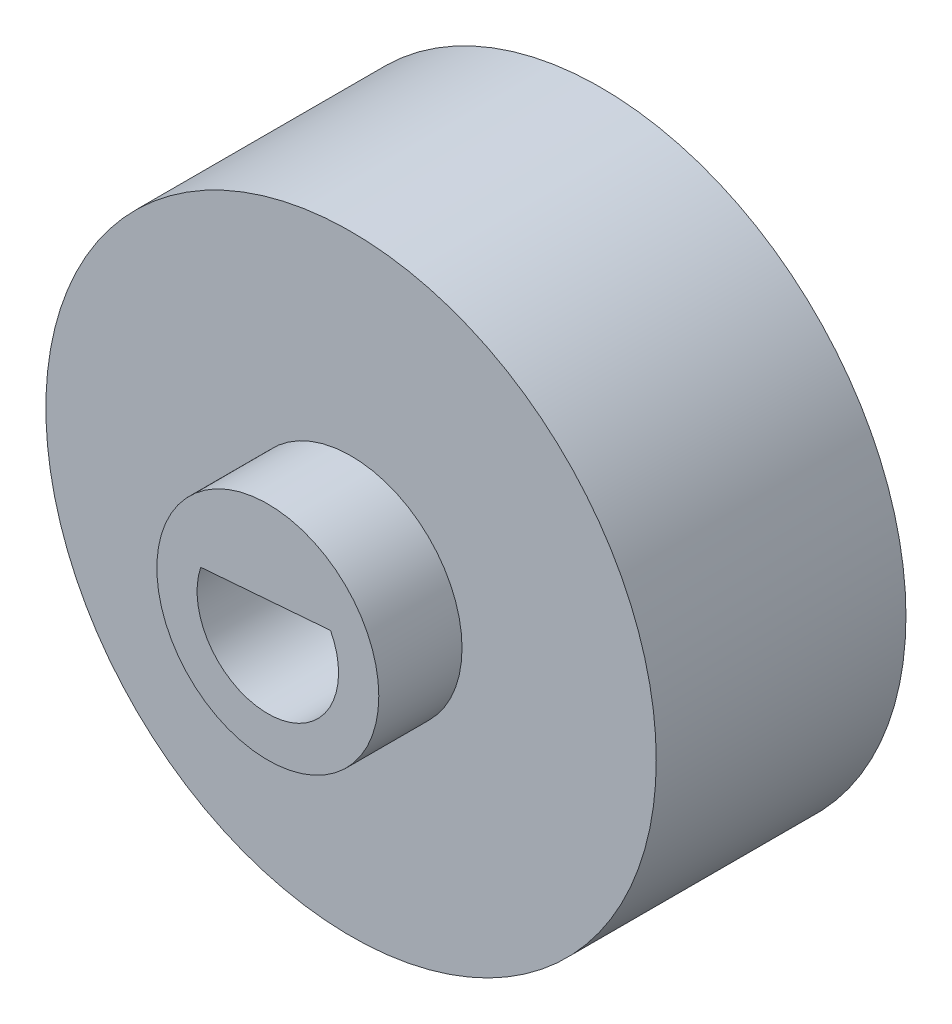
SolidWorks part; units mm, degrees
ref_plane "前视基准面" through (0, 0, 0) normal (0, 0, 1) x (1, 0, 0)
ref_plane "上视基准面" through (0, 0, 0) normal (0, 1, 0) x (1, 0, 0)
ref_plane "右视基准面" through (0, 0, 0) normal (1, 0, 0) x (0, 0, -1)
other "Configuration Table"
sketch "草图1" plane through (0, 0, 0) normal (0, 0, 1) x (1, 0, 0)
  line L0 (4.5201, 2.3619) -> (-4.8339, 1.6257)
  circle A0 centre (0, 0) radius 8
  arc A1 (-4.8339, 1.6257) -> (4.5201, 2.3619) centre (0, 0) ccw
extrude "凸台-拉伸1" add sketch "草图1" along normal blind 24
sketch "草图2" plane through (0, 0, 0) normal (0, 0, 1) x (1, 0, 0)
  circle A0 centre (0, 0) radius 22
  circle A1 centre (0, 0) radius 8
extrude "凸台-拉伸2" add sketch "草图2" along normal blind 18
sketch "草图3" plane through (0, 0, 0) normal (0, 0, 1) x (1, 0, 0)
  line L0 (17.4237, 1.6329) -> (18.7119, 1.6329)
  line L1 (18.7119, 1.6329) -> (18.7557, 1.7557)
  line L2 (18.7557, 1.7557) -> (18.8873, 1.754)
  line L3 (18.8873, 1.754) -> (19.1059, 1.7366)
  line L4 (19.1059, 1.7366) -> (19.4097, 1.7366)
  line L5 (19.4097, 1.7366) -> (19.7954, 1.7366)
  line L6 (19.7954, 1.7366) -> (20.2587, 1.7366)
  line L7 (20.2587, 1.7366) -> (20.7568, 1.2385)
  line L8 (20.7568, 1.2385) -> (21.395, 1.2385)
  line L9 (21.9651, 1.2385) -> (21.9939, 0.5176)
  line L10 (21.9939, 0.5176) -> (22, 0)
  line L11 (22, 0) -> (21.9939, -0.5176)
  line L12 (21.9939, -0.5176) -> (21.9756, -1.0349)
  line L13 (21.9756, -1.0349) -> (20.7568, -1.0349)
  line L14 (20.7568, -1.0349) -> (20.2587, -1.533)
  line L15 (20.2587, -1.533) -> (19.7954, -1.533)
  line L16 (19.7954, -1.533) -> (19.4097, -1.533)
  line L17 (19.4097, -1.533) -> (19.1059, -1.533)
  line L18 (19.1059, -1.533) -> (18.8873, -1.754)
  line L19 (18.8873, -1.754) -> (18.7557, -1.7557)
  line L20 (18.7557, -1.7557) -> (18.7119, -1.7536)
  line L21 (18.7119, -1.7536) -> (17.4237, -1.6329)
  arc A0 (17.4237, -1.6329) -> (17.4237, 1.6329) centre (0, 0) ccw
  circle A1 centre (0, 0) radius 22 construction
